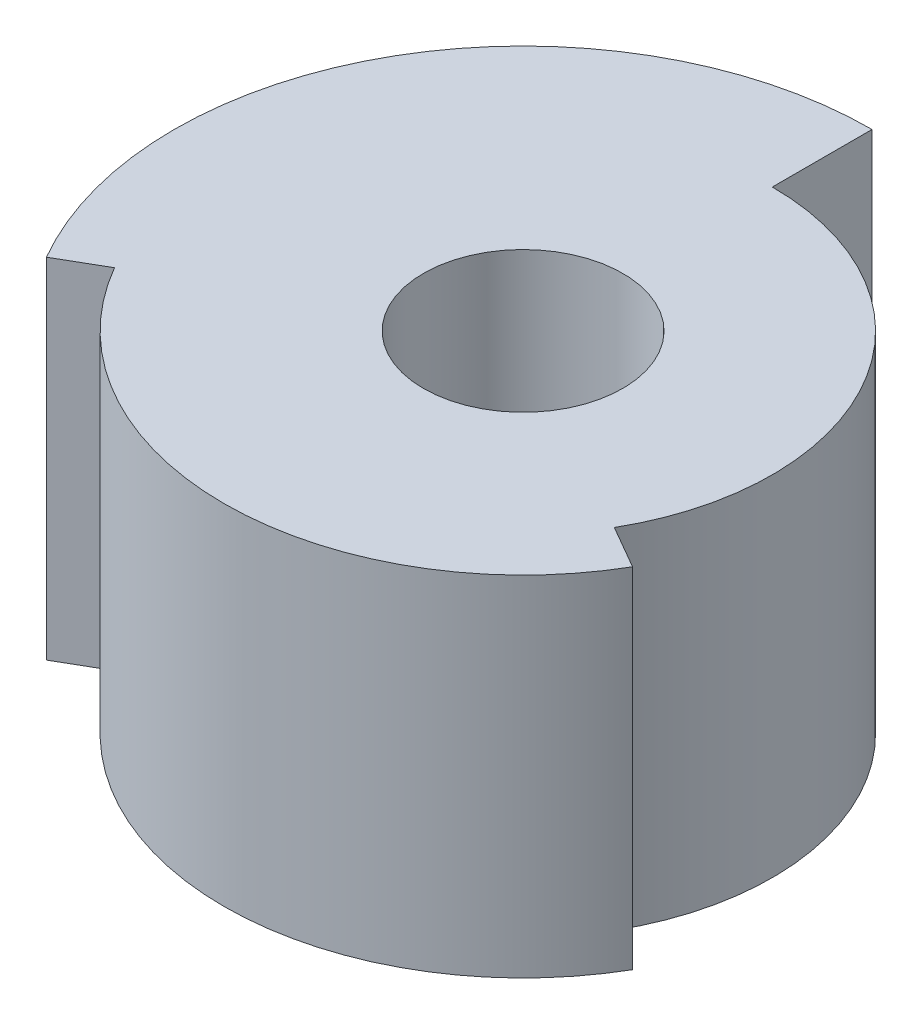
SolidWorks part; units mm, degrees
ref_plane "Front Plane" through (0, 0, 0) normal (0, 0, 1) x (1, 0, 0)
ref_plane "Top Plane" through (0, 0, 0) normal (0, 1, 0) x (1, 0, 0)
ref_plane "Right Plane" through (0, 0, 0) normal (1, 0, 0) x (0, 0, -1)
sketch "Sketch1" plane through (0, 0, 0) normal (0, 1, 0) x (1, 0, 0)
  line L0 (0, 25) -> (0, 30)
  line L1 (21.6506, -12.5) -> (25.9808, -15)
  line L2 (-25.9808, -15) -> (-30.3109, -17.5)
  line L3 (0, 30) -> (0, 35)
  circle A0 centre (0, 0) radius 30 construction
  circle A1 centre (0, 0) radius 35 construction
  circle A2 centre (0, 0) radius 25 construction
  arc A3 (0, 25) -> (21.6506, -12.5) centre (0, 0) cw
  arc A4 (25.9808, -15) -> (-25.9808, -15) centre (0, 0) cw
  arc A5 (-30.3109, -17.5) -> (0, 35) centre (0, 0) cw
  circle A6 centre (0, 0) radius 10
  dimension "D1" = 60
  dimension "D2" = 70
  dimension "D3" = 50
  dimension "D4" = 120
  dimension "D6" = 20
  dimension "D5" = 120
extrude "Boss-Extrude1" add sketch "Sketch1" along normal blind 35 contours A0
